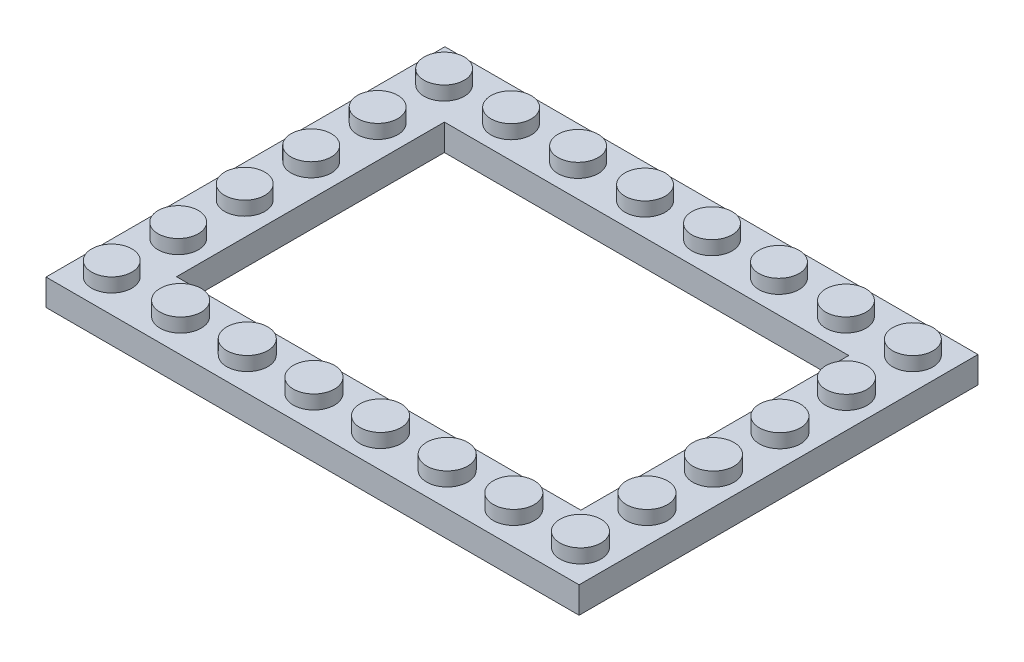
SolidWorks part; units mm, degrees
ref_plane "Front Plane" through (0, 0, 0) normal (0, 0, 1) x (1, 0, 0)
ref_plane "Top Plane" through (0, 0, 0) normal (0, 1, 0) x (1, 0, 0)
ref_plane "Right Plane" through (0, 0, 0) normal (1, 0, 0) x (0, 0, -1)
sketch "Sketch1" plane through (0, 0, 0) normal (0, 0, 1) x (1, 0, 0)
  line L0 (0, 0) -> (63.8, 0)
  line L1 (63.8, 0) -> (63.8, 3.16)
  line L2 (63.8, 3.16) -> (0, 3.16)
  line L3 (0, 3.16) -> (0, 0)
  dimension "D1" = 63.8
  dimension "D2" = 3.16
extrude "Boss-Extrude1" add sketch "Sketch1" against normal blind 47.74
sketch "Sketch2" plane through (0, 3.16, 0) normal (0, 1, 0) x (1, 0, 0)
  line L0 (7.78, 39.9) -> (56.17, 39.9)
  line L1 (56.17, 39.9) -> (56.17, 7.84)
  line L2 (56.17, 7.84) -> (7.78, 7.84)
  line L3 (7.78, 7.84) -> (7.78, 39.9)
  line L4 (63.8, 47.74) -> (0, 47.74) construction
  line L5 (63.8, 0) -> (0, 0) construction
  line L6 (63.8, 47.74) -> (63.8, 0) construction
  line L7 (0, 47.74) -> (0, 0) construction
  dimension "D1" = 7.84
  dimension "D2" = 7.84
  dimension "D3" = 7.63
  dimension "D4" = 7.78
extrude "Cut-Extrude1" cut sketch "Sketch2" against normal through all
sketch "Sketch3" plane through (0, 3.16, 0) normal (0, 1, 0) x (1, 0, 0)
  line L1 (0, 47.74) -> (0, 0) construction
  line L2 (63.8, 47.74) -> (0, 47.74) construction
  line L4 (63.8, 0) -> (0, 0) construction
  line L5 (63.8, 47.74) -> (63.8, 0) construction
  circle A0 centre (3.89, 43.7617) radius 2.41
  circle A1 centre (11.9036, 43.7617) radius 2.41
  circle A2 centre (19.9171, 43.7617) radius 2.41
  circle A3 centre (27.9307, 43.7617) radius 2.41
  circle A4 centre (35.9443, 43.7617) radius 2.41
  circle A5 centre (43.9579, 43.7617) radius 2.41
  circle A6 centre (51.9714, 43.7617) radius 2.41
  circle A7 centre (59.985, 43.7617) radius 2.41
  circle A8 centre (3.89, 35.805) radius 2.41
  circle A9 centre (3.89, 27.8483) radius 2.41
  circle A10 centre (3.89, 19.8917) radius 2.41
  circle A11 centre (3.89, 11.935) radius 2.41
  circle A12 centre (3.89, 3.9783) radius 2.41
  circle A13 centre (59.985, 3.9783) radius 2.46
  circle A14 centre (59.985, 11.935) radius 2.46
  circle A15 centre (59.985, 19.8917) radius 2.46
  circle A16 centre (59.985, 27.8483) radius 2.46
  circle A17 centre (59.985, 35.805) radius 2.46
  circle A18 centre (52.01, 3.9783) radius 2.46
  circle A19 centre (44.035, 3.9783) radius 2.46
  circle A20 centre (36.06, 3.9783) radius 2.46
  circle A21 centre (28.085, 3.9783) radius 2.46
  circle A22 centre (20.11, 3.9783) radius 2.46
  circle A23 centre (12.135, 3.9783) radius 2.46
  dimension "D1" = 4.82
  dimension "D2" = 3.89
  dimension "D3" = 3.9783
  dimension "D5" = 4.92
  dimension "D10" = 7.975
  dimension "D11" = 7.9567
  dimension "D12" = 6
  dimension "D6" = 5
  dimension "D7" = 3.9783
  dimension "D8" = 3.815
  dimension "D9" = 7
  dimension "D4" = 8
extrude "Boss-Extrude2" add sketch "Sketch3" along normal blind 1.67
shell "Shell1" thickness 1.68
sketch "Sketch4" plane through (0, 1.48, 0) normal (0, -1, 0) x (1, 0, 0)
  line L2 (0, 0) -> (63.8, 0) construction
  line L4 (0, -47.74) -> (0, 0) construction
  line L5 (0, -47.74) -> (63.8, -47.74) construction
  line L6 (63.8, -47.74) -> (63.8, 0) construction
  circle A2 centre (7.88, -3.92) radius 1.485
  circle A3 centre (3.89, -3.9783) radius 0.73 construction
  circle A4 centre (3.89, -31.835) radius 1.485
  circle A5 centre (15.86, -3.92) radius 1.485
  circle A6 centre (23.84, -3.92) radius 1.485
  circle A7 centre (31.82, -3.92) radius 1.485
  circle A8 centre (39.8, -3.92) radius 1.485
  circle A9 centre (47.78, -3.92) radius 1.485
  circle A10 centre (55.76, -3.92) radius 1.485
  circle A11 centre (7.88, -3.92) radius 1.04
  circle A18 centre (15.86, -3.92) radius 1.04
  circle A19 centre (23.84, -3.92) radius 1.04
  circle A20 centre (31.82, -3.92) radius 1.04
  circle A21 centre (39.8, -3.92) radius 1.04
  circle A22 centre (47.78, -3.92) radius 1.04
  circle A23 centre (55.76, -3.92) radius 1.04
  circle A24 centre (3.89, -23.875) radius 1.485
  circle A25 centre (7.9186, -43.82) radius 1.485
  circle A27 centre (11.9036, -43.7617) radius 0.73 construction
  circle A29 centre (15.8986, -43.82) radius 1.485
  circle A30 centre (23.8786, -43.82) radius 1.485
  circle A31 centre (31.8586, -43.82) radius 1.485
  circle A32 centre (39.8386, -43.82) radius 1.485
  circle A33 centre (47.8186, -43.82) radius 1.485
  circle A34 centre (55.7986, -43.82) radius 1.485
  circle A35 centre (7.9186, -43.82) radius 1.04
  circle A36 centre (15.8986, -43.82) radius 1.04
  circle A37 centre (23.8786, -43.82) radius 1.04
  circle A38 centre (31.8586, -43.82) radius 1.04
  circle A39 centre (39.8386, -43.82) radius 1.04
  circle A40 centre (47.8186, -43.82) radius 1.04
  circle A41 centre (55.7986, -43.82) radius 1.04
  circle A42 centre (59.985, -43.7617) radius 0.73 construction
  circle A43 centre (59.985, -39.7817) radius 1.485
  circle A44 centre (59.985, -31.8217) radius 1.485
  circle A45 centre (59.985, -23.8617) radius 1.485
  circle A46 centre (59.985, -15.9017) radius 1.485
  circle A47 centre (59.985, -7.9417) radius 1.485
  circle A48 centre (59.985, -39.7817) radius 1.04
  circle A49 centre (59.985, -31.8217) radius 1.04
  circle A50 centre (59.985, -23.8617) radius 1.04
  circle A51 centre (59.985, -15.9017) radius 1.04
  circle A52 centre (59.985, -7.9417) radius 1.04
  circle A53 centre (3.89, -39.795) radius 1.485
  circle A54 centre (3.89, -15.915) radius 1.485
  circle A55 centre (3.89, -7.955) radius 1.485
  circle A57 centre (3.89, -11.935) radius 0.73 construction
  circle A59 centre (3.89, -39.795) radius 1.04
  circle A60 centre (3.89, -31.835) radius 1.04
  circle A61 centre (3.89, -23.875) radius 1.04
  circle A62 centre (3.89, -15.915) radius 1.04
  circle A63 centre (3.89, -7.955) radius 1.04
  dimension "D1" = 2.97
  dimension "D2" = 3.99
  dimension "D3" = 3.92
  dimension "D5" = 2.08
  dimension "D8" = 7.98
  dimension "D6" = 7.98
  dimension "D9" = 2.97
  dimension "D10" = 3.985
  dimension "D12" = 7
  dimension "D13" = 7.98
  dimension "D14" = 2.08
  dimension "D16" = 7.98
  dimension "D17" = 2.97
  dimension "D18" = 3.815
  dimension "D19" = 3.98
  dimension "D21" = 7.96
  dimension "D22" = 2.08
  dimension "D24" = 7.96
  dimension "D25" = 3.89
  dimension "D26" = 2.97
  dimension "D28" = 7.96
  dimension "D29" = 3.98
  dimension "D30" = 2.08
  dimension "D32" = 7.96
  dimension "D11" = 3.92
  dimension "D20" = 5
  dimension "D4" = 7
  dimension "D7" = 7
  dimension "D15" = 7
  dimension "D23" = 5
  dimension "D27" = 5
  dimension "D31" = 5
extrude "Boss-Extrude3" add sketch "Sketch4" along normal blind 1.23
